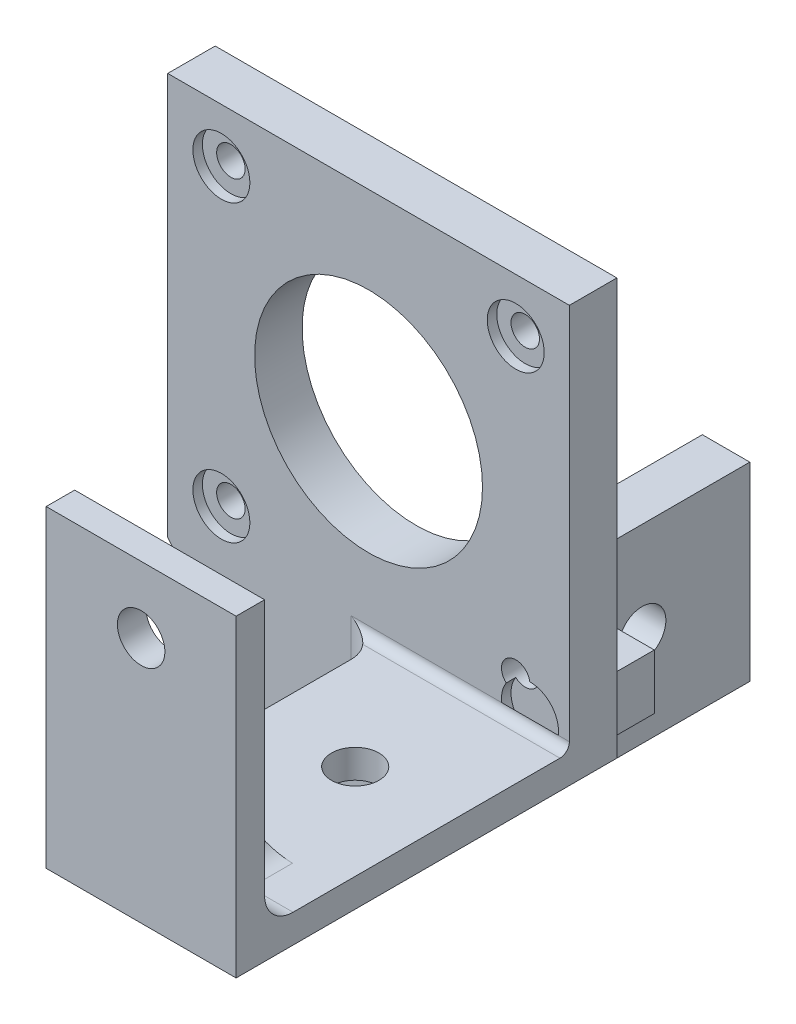
SolidWorks part; units mm, degrees
ref_plane "前视基准面" through (0, 0, 0) normal (0, 0, 1) x (1, 0, 0)
ref_plane "上视基准面" through (0, 0, 0) normal (0, 1, 0) x (1, 0, 0)
ref_plane "右视基准面" through (0, 0, 0) normal (1, 0, 0) x (0, 0, -1)
other "Configuration Table"
sketch "草图1" plane through (0, 0, 0) normal (0, 0, 1) x (1, 0, 0)
  line L0 (21.15, 0) -> (21.15, -42.3) construction
  line L1 (0, 0) -> (42.3, 0)
  line L2 (0, 0) -> (0, -42.3)
  line L4 (42.3, 0) -> (42.3, -42.3)
  line L5 (0, -21.15) -> (42.3, -21.15) construction
  line L6 (22.3, -63.8) -> (17.3, -63.8)
  line L7 (17.3, -63.8) -> (0, -42.3)
  line L8 (22.3, -63.8) -> (22.3, -43.8)
  line L9 (22.3, -43.8) -> (42.3, -43.8)
  line L10 (42.3, -43.8) -> (42.3, -42.3)
  circle A0 centre (21.15, -21.15) radius 12
  circle A2 centre (5.65, -5.65) radius 1.5
  circle A3 centre (36.65, -5.65) radius 1.5
  circle A4 centre (36.65, -36.65) radius 1.5
  circle A5 centre (5.65, -36.65) radius 1.5
  dimension "D3" = 24
  dimension "D4" = 3
  dimension "D5" = 5
  dimension "D1" = 42.3
  dimension "D2" = 42.3
  dimension "D6" = 5.65
  dimension "D7" = 5.65
  dimension "D8" = 20
  dimension "D9" = 1.5
extrude "凸台-拉伸1" add sketch "草图1" along normal blind 5
sketch "草图2" plane through (0, 0, 0) normal (0, 0, -1) x (-1, 0, 0)
  line L1 (-17.3, -43.8) -> (-17.3, -63.8)
  line L2 (-17.3, -63.8) -> (-22.3, -63.8)
  line L3 (-22.3, -63.8) -> (-22.3, -43.8)
  line L4 (-22.3, -43.8) -> (-17.3, -43.8)
extrude "凸台-拉伸2" add sketch "草图2" along normal blind 34
fillet "圆角2" radius 10 1 edges at (17.3, -53.8, 0)
sketch "草图4" plane through (0, 0, 5) normal (0, 0, 1) x (1, 0, 0)
  line L0 (42.3, -40.8) -> (22.3, -40.8)
  line L1 (42.3, -43.8) -> (42.3, 0) construction
  line L2 (22.3, -40.8) -> (22.3, -43.8)
  line L3 (22.3, -43.8) -> (42.3, -43.8)
  line L4 (42.3, -43.8) -> (42.3, -40.8)
  dimension "D1" = 3
extrude "凸台-拉伸3" add sketch "草图4" along normal blind 35.1
fillet "圆角3" radius 1 1 edges at (32.3, -40.8, 5)
sketch "草图5" plane through (0, -40.8, 0) normal (0, 1, 0) x (1, 0, 0)
  line L0 (22.3, -40.1) -> (42.3, -40.1)
  line L1 (42.3, -40.1) -> (42.3, -37.1)
  line L2 (42.3, -40.1) -> (42.3, -6) construction
  line L3 (42.3, -37.1) -> (22.3, -37.1)
  line L4 (22.3, -40.1) -> (22.3, -6) construction
  line L5 (22.3, -37.1) -> (22.3, -40.1)
  dimension "D1" = 3
  dimension "D2" = 20
extrude "凸台-拉伸4" add sketch "草图5" along normal blind 30
ref_plane "基准面1" through (32.3, 0, 0) normal (1, 0, 0) x (0, 0, -1)
sketch "草图8" plane through (32.3, 0, 0) normal (1, 0, 0) x (0, 0, -1)
  line L0 (-37.1, -25.8) -> (-29.6519, -40.8)
  line L1 (-37.1, -10.8) -> (-37.1, -40.8) construction
  line L2 (-37.1, -40.8) -> (-6, -40.8) construction
rib "筋1" sketch "草图8" sketch "草图8" thickness 5 extrusion direction parallel to sketch draft on no parameters "D1"=5
sketch "草图9" plane through (0, 0, 40.1) normal (0, 0, 1) x (1, 0, 0)
  line L0 (32.3, -24.09) -> (32.3, 24.09) construction
  circle A0 centre (32.3, -17.7955) radius 2.5
  dimension "D1" = 5
extrude "切除-拉伸1" cut sketch "草图9" against normal blind 30
sketch "草图10" plane through (0, -40.8, 0) normal (0, 1, 0) x (1, 0, 0)
  line L0 (32.3, -24.09) -> (32.3, 24.09) construction
  circle A0 centre (32.3, -17.5551) radius 2.5
  dimension "D1" = 5
extrude "切除-拉伸2" cut sketch "草图10" against normal blind 30
sketch "草图11" plane through (17.3, 0, 0) normal (-1, 0, 0) x (0, 0, 1)
  circle A0 centre (-22.6582, -53.8) radius 2.5
  dimension "D1" = 5
extrude "切除-拉伸3" cut sketch "草图11" against normal blind 30
sketch "草图12" plane through (0, 0, 5) normal (0, 0, 1) x (1, 0, 0)
  circle A0 centre (5.65, -5.65) radius 3
  circle A1 centre (36.65, -5.65) radius 3
  circle A2 centre (5.65, -36.65) radius 3
  circle A3 centre (38.15, -39.4193) radius 3
  dimension "D1" = 6
  dimension "D2" = 6
  dimension "D3" = 6
  dimension "D4" = 6
extrude "切除-拉伸4" cut sketch "草图12" against normal blind 1
sketch "草图13" plane through (17.3, 0, 0) normal (-1, 0, 0) x (0, 0, 1)
  circle A0 centre (-22.6582, -53.8) radius 4
  dimension "D1" = 8
extrude "切除-拉伸5" cut sketch "草图13" against normal blind 1
sketch "草图14" plane through (22.3, 0, 0) normal (1, 0, 0) x (0, 0, -1)
  line L0 (-5, -63.8) -> (-5, -43.8) construction
  line L1 (18.9375, -56.7) -> (-5, -56.7)
  line L3 (18.9375, -50.9) -> (-5, -50.9)
  line L4 (-5, -56.7) -> (-5, -50.9)
  line L7 (18.9375, -50.9) -> (18.9375, -56.7)
  line L8 (18.9375, -54.8452) -> (-5, -50.9) construction
  line L9 (18.9375, -55.2851) -> (-5, -56.7) construction
  point P0 (22.6582, -53.8)
  dimension "D1" = 5.8
  dimension "D2" = 2.9
extrude "凸台-拉伸5" add sketch "草图14" along normal blind 5
fillet "圆角4" radius 3 8 edges at (26.05, -40.8, 37.1) (38.55, -40.8, 37.1) (34.8, -40.8, 33.3759) (34.8, -33.3, 37.1) (29.8, -40.8, 33.3759) (29.8, -33.3, 37.1) (22.3, -41.8, 5) (14.8, -43.8, 0)
